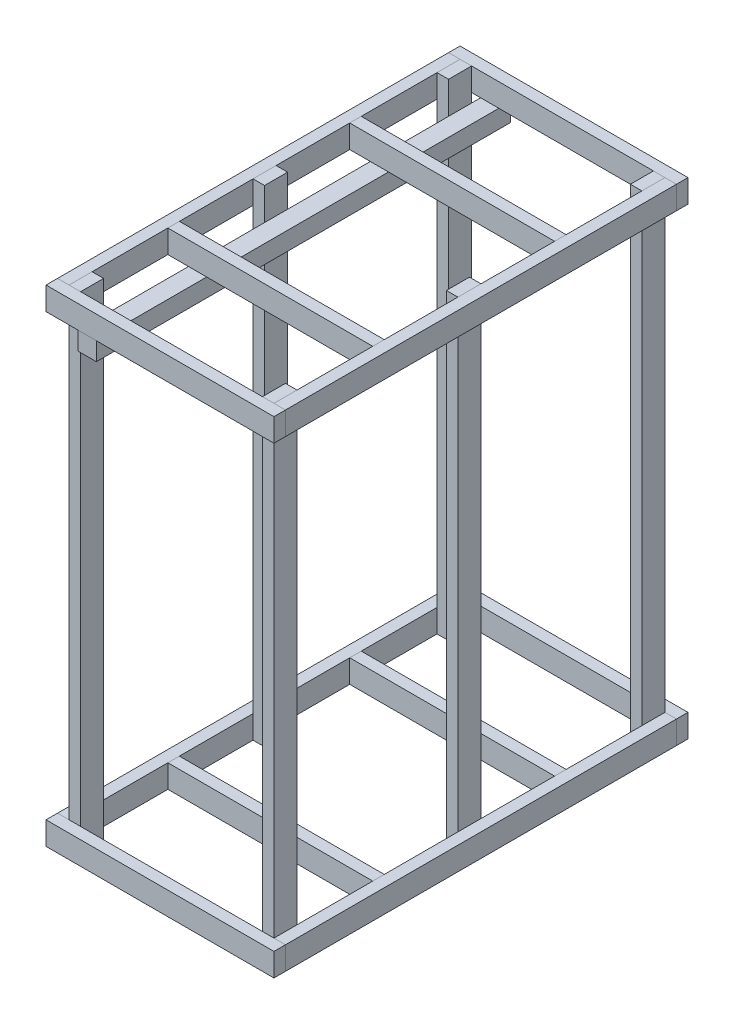
SolidWorks part; units mm, degrees
ref_plane "正面" through (0, 0, 0) normal (0, 0, 1) x (1, 0, 0)
ref_plane "平面" through (0, 0, 0) normal (0, 1, 0) x (1, 0, 0)
ref_plane "右側面" through (0, 0, 0) normal (1, 0, 0) x (0, 0, -1)
sketch "元ライン_正面" plane through (0, 0, 0) normal (0, 0, 1) x (1, 0, 0)
  line B0 (-135, 666) -> (-135, 0)
  line B1 (-135, 666) -> (105, 666)
  line B2 (105, 696) -> (135, 696)
  line B3 (105, 666) -> (105, 696)
  line B4 (-135, 0) -> (135, 0)
  line B5 (135, 696) -> (135, 0)
sketch_block_instance "ﾌﾞﾛｯｸ1-1"
sketch_block "ﾌﾞﾛｯｸ1"
sketch "元ライン_側面" plane through (0, 0, 0) normal (1, 0, 0) x (0, 0, -1)
  line B0 (-307.5, 696) -> (-307.5, 0)
  line B1 (-307.5, 696) -> (307.5, 696)
  line B2 (-307.5, 0) -> (307.5, 0)
  line B3 (307.5, 0) -> (307.5, 696)
sketch_block_instance "ﾌﾞﾛｯｸ2-1"
sketch_block "ﾌﾞﾛｯｸ2"
sketch "元ライン_平面" plane through (0, 0, 0) normal (0, 1, 0) x (1, 0, 0)
  line B0 (135, 307.5) -> (-135, 307.5)
  line B1 (-135, 307.5) -> (-135, -307.5)
  line B2 (-135, -307.5) -> (135, -307.5)
  line B3 (135, -307.5) -> (135, 307.5)
sketch_block_instance "ﾌﾞﾛｯｸ3-1"
sketch_block "ﾌﾞﾛｯｸ3"
sketch "マスター_平面" plane through (0, 0, 0) normal (0, 1, 0) x (1, 0, 0)
  line L10 (-188, 341.5) -> (-188, -341.5)
  line L11 (-188, -341.5) -> (188, -341.5)
  line L12 (188, -341.5) -> (188, 341.5)
  line L13 (188, 341.5) -> (-188, 341.5)
  line L14 (-135, -307.5) -> (135, -307.5) construction
  line L15 (135, 307.5) -> (-135, 307.5) construction
  line L16 (135, -307.5) -> (135, 307.5) construction
  line L17 (0, 307.5) -> (0, -307.5) construction
  line L18 (-188, -322.5) -> (188, -322.5)
  line L19 (169, -322.5) -> (169, 322.5)
  line L20 (188, 322.5) -> (-188, 322.5)
  line L21 (-169, 322.5) -> (-169, -322.5)
  line L22 (169, 322.5) -> (-169, 322.5) construction
  line L23 (-169, -322.5) -> (169, -322.5) construction
  line L25 (-169, 322.5) -> (-150, 322.5)
  line L26 (-169, 322.5) -> (-169, 284.5)
  line L27 (-169, 284.5) -> (-150, 284.5)
  line L28 (-150, 322.5) -> (-150, 284.5)
  dimension "D1" = 15
  dimension "D3" = 15
  dimension "D4" = 34
  dimension "D5" = 19
  dimension "D6" = 38
  dimension "D2" = 19
sketch "マスター_正面" plane through (0, 0, 0) normal (0, 0, 1) x (1, 0, 0)
  line L9 (-135, 0) -> (135, 0) construction
  line L10 (105, 696) -> (135, 696) construction
  line B0 (-188, -20) -> (-169, -20)
  line B1 (-188, -20) -> (-188, -58)
  line B2 (-188, -58) -> (-169, -58)
  line B3 (-169, -20) -> (-169, -58)
  line B4 (-188, 744) -> (-169, 744)
  line B5 (-188, 744) -> (-188, 706)
  line B6 (-188, 706) -> (-169, 706)
  line B7 (-169, 744) -> (-169, 706)
  line B8 (169, 744) -> (188, 744)
  line B9 (169, 744) -> (169, 706)
  line B10 (169, 706) -> (188, 706)
  line B11 (188, 744) -> (188, 706)
  line B12 (169, -20) -> (188, -20)
  line B13 (169, -20) -> (169, -58)
  line B14 (169, -58) -> (188, -58)
  line B15 (188, -20) -> (188, -58)
  dimension "D1" = 20
  dimension "D2" = 10
sketch_block_instance "ﾌﾞﾛｯｸ4-1"
sketch_block "ﾌﾞﾛｯｸ4" parameters "D1"=19, "D2"=38
sketch_block_instance "ﾌﾞﾛｯｸ4-2"
sketch_block_instance "ﾌﾞﾛｯｸ4-3"
sketch_block_instance "ﾌﾞﾛｯｸ4-4"
sketch "マスター_側面" plane through (0, 0, 0) normal (1, 0, 0) x (0, 0, -1)
  point P0 (350.1615, 370.0994)
  line B0 (-341.5, -20) -> (-322.5, -20)
  line B1 (-341.5, -20) -> (-341.5, -58)
  line B2 (-341.5, -58) -> (-322.5, -58)
  line B3 (-322.5, -20) -> (-322.5, -58)
  line B4 (322.5, -20) -> (341.5, -20)
  line B5 (322.5, -20) -> (322.5, -58)
  line B6 (322.5, -58) -> (341.5, -58)
  line B7 (341.5, -20) -> (341.5, -58)
  line B8 (322.5, 744) -> (341.5, 744)
  line B9 (322.5, 744) -> (322.5, 706)
  line B10 (322.5, 706) -> (341.5, 706)
  line B11 (341.5, 744) -> (341.5, 706)
  line B12 (-341.5, 744) -> (-322.5, 744)
  line B13 (-341.5, 744) -> (-341.5, 706)
  line B14 (-341.5, 706) -> (-322.5, 706)
  line B15 (-322.5, 744) -> (-322.5, 706)
sketch_block_instance "ﾌﾞﾛｯｸ5-1"
sketch_block "ﾌﾞﾛｯｸ5" parameters "D1"=19, "D2"=38
sketch_block_instance "ﾌﾞﾛｯｸ5-2"
sketch_block_instance "ﾌﾞﾛｯｸ5-3"
sketch_block_instance "ﾌﾞﾛｯｸ5-4"
sketch "ｽｹｯﾁ6" plane through (0, 0, 0) normal (0, 0, 1) x (1, 0, 0)
  line L4 (-169, -20) -> (-169, -58) construction
  line L5 (-188, -58) -> (-169, -58) construction
  line L6 (-188, -20) -> (-188, -58) construction
  line L7 (-188, -20) -> (-169, -20) construction
  line L8 (169, -58) -> (188, -58) construction
  line L9 (188, -20) -> (188, -58) construction
  line L10 (169, -20) -> (169, -58) construction
  line L11 (169, -20) -> (188, -20) construction
  line L12 (-169, -20) -> (-169, -58)
  line L13 (-188, -58) -> (-169, -58)
  line L14 (-188, -20) -> (-188, -58)
  line L15 (-188, -20) -> (-169, -20)
  line L16 (188, 744) -> (188, 706) construction
  line L17 (169, 706) -> (188, 706) construction
  line L18 (169, 744) -> (188, 744) construction
  line L19 (169, 744) -> (169, 706) construction
  line L20 (-188, 706) -> (-169, 706) construction
  line L21 (-169, 744) -> (-169, 706) construction
  line L22 (-188, 744) -> (-169, 744) construction
  line L23 (-188, 744) -> (-188, 706) construction
  line L24 (169, -58) -> (188, -58)
  line L25 (188, -20) -> (188, -58)
  line L26 (169, -20) -> (169, -58)
  line L27 (169, -20) -> (188, -20)
  line L28 (188, 744) -> (188, 706)
  line L29 (169, 706) -> (188, 706)
  line L30 (169, 744) -> (188, 744)
  line L31 (169, 744) -> (169, 706)
  line L32 (-188, 706) -> (-169, 706)
  line L33 (-169, 744) -> (-169, 706)
  line L34 (-188, 744) -> (-169, 744)
  line L35 (-188, 744) -> (-188, 706)
extrude "ﾎﾞｽ - 押し出し1" add sketch "ｽｹｯﾁ6" against normal up to vertex (322.5 mm away) and the other way up to vertex (322.5 mm away) up to point (188, 0, -322.5) other way up to point (188, 0, 322.5)
sketch "ｽｹｯﾁ8" plane through (0, 0, 0) normal (1, 0, 0) x (0, 0, -1)
  line L4 (-341.5, -20) -> (-341.5, -58) construction
  line L5 (-341.5, -58) -> (-322.5, -58) construction
  line L6 (-322.5, -20) -> (-322.5, -58) construction
  line L7 (-341.5, -20) -> (-322.5, -20) construction
  line L8 (-341.5, 706) -> (-322.5, 706) construction
  line L9 (-322.5, 744) -> (-322.5, 706) construction
  line L10 (-341.5, 744) -> (-322.5, 744) construction
  line L11 (-341.5, 744) -> (-341.5, 706) construction
  line L12 (-341.5, -20) -> (-341.5, -58)
  line L13 (-341.5, -58) -> (-322.5, -58)
  line L14 (-322.5, -20) -> (-322.5, -58)
  line L15 (-341.5, -20) -> (-322.5, -20)
  line L16 (322.5, 706) -> (341.5, 706) construction
  line L17 (341.5, 744) -> (341.5, 706) construction
  line L18 (322.5, 744) -> (341.5, 744) construction
  line L19 (322.5, 744) -> (322.5, 706) construction
  line L20 (322.5, -58) -> (341.5, -58) construction
  line L21 (341.5, -20) -> (341.5, -58) construction
  line L22 (322.5, -20) -> (341.5, -20) construction
  line L23 (322.5, -20) -> (322.5, -58) construction
  line L24 (-341.5, 706) -> (-322.5, 706)
  line L25 (-322.5, 744) -> (-322.5, 706)
  line L26 (-341.5, 744) -> (-322.5, 744)
  line L27 (-341.5, 744) -> (-341.5, 706)
  line L28 (322.5, 706) -> (341.5, 706)
  line L29 (341.5, 744) -> (341.5, 706)
  line L30 (322.5, 744) -> (341.5, 744)
  line L31 (322.5, 744) -> (322.5, 706)
  line L32 (322.5, -58) -> (341.5, -58)
  line L33 (341.5, -20) -> (341.5, -58)
  line L34 (322.5, -20) -> (341.5, -20)
  line L35 (322.5, -20) -> (322.5, -58)
extrude "ﾎﾞｽ - 押し出し2" add sketch "ｽｹｯﾁ8" along normal up to vertex (188 mm away) and the other way up to surface (188 mm away) separate body up to point (188, 0, 341.5) other way up to face at (-188, -39, 0)
sketch "ｽｹｯﾁ9" plane through (0, 0, 0) normal (0, 1, 0) x (1, 0, 0)
  line L0 (-169, 284.5) -> (-150, 284.5) construction
  line L1 (-169, 322.5) -> (-169, 284.5) construction
  line L2 (-150, 322.5) -> (-150, 284.5) construction
  line L3 (-169, 322.5) -> (-150, 322.5) construction
  line L4 (-169, 284.5) -> (-150, 284.5)
  line L5 (-169, 322.5) -> (-169, 284.5)
  line L6 (-150, 322.5) -> (-150, 284.5)
  line L7 (-169, 322.5) -> (-150, 322.5)
  line L8 (-169, -322.5) -> (-150, -322.5)
  line L9 (-169, -284.5) -> (-169, -322.5)
  line L10 (-169, -284.5) -> (-150, -284.5)
  line L11 (-150, -284.5) -> (-150, -322.5)
  line L12 (150, 284.5) -> (169, 284.5)
  line L13 (150, 322.5) -> (150, 284.5)
  line L14 (150, 322.5) -> (169, 322.5)
  line L15 (169, 322.5) -> (169, 284.5)
  line L16 (150, -322.5) -> (169, -322.5)
  line L17 (150, -284.5) -> (150, -322.5)
  line L18 (150, -284.5) -> (169, -284.5)
  line L19 (169, -284.5) -> (169, -322.5)
  line L20 (169, -322.5) -> (169, 322.5) construction
  line L21 (-188, -322.5) -> (188, -322.5) construction
  line L22 (-169, 19) -> (-169, -19)
  line L23 (-169, 19) -> (-150, 19)
  line L24 (-150, 19) -> (-150, -19)
  line L25 (-169, -19) -> (-150, -19)
  line L26 (150, 19) -> (150, -19)
  line L27 (150, 19) -> (169, 19)
  line L28 (169, 19) -> (169, -19)
  line L29 (150, -19) -> (169, -19)
  line L31 (-169, 322.5) -> (-169, -322.5) construction
  line L32 (-169, 0) -> (169, 0) construction
  line L33 (169, 322.5) -> (169, -322.5) construction
  point P28 (0, 0)
  point P31 (-169, 0)
extrude "縦材" add sketch "ｽｹｯﾁ9" along normal up to vertex and the other way up to vertex separate body
sketch "ｽｹｯﾁ10" plane through (0, 0, 0) normal (0, 0, 1) x (1, 0, 0)
  line L0 (-135, 666) -> (-135, 0) construction
  line L1 (-135, 706) -> (-105, 706)
  line L2 (-135, 706) -> (-135, 676)
  line L3 (-135, 676) -> (-105, 676)
  line L4 (-105, 706) -> (-105, 676)
  point P4 (-113.9049, 706)
  dimension "D1" = 30
extrude "ﾎﾞｽ - 押し出し4" add sketch "ｽｹｯﾁ10" along normal up to vertex and the other way up to vertex separate body
sketch "ｽｹｯﾁ11" plane through (0, 0, 0) normal (1, 0, 0) x (0, 0, -1)
  line L0 (-307.5, 696) -> (307.5, 696) construction
  line L1 (0, 696) -> (0, 0) construction
  line L5 (-307.5, 696) -> (307.5, 696) construction
  point P7 (0, 696)
  point P8 (-150, 706)
  line B0 (-159.5, 744) -> (-140.5, 744)
  line B1 (-159.5, 744) -> (-159.5, 706)
  line B2 (-159.5, 706) -> (-140.5, 706)
  line B3 (-140.5, 744) -> (-140.5, 706)
  line B4 (-159.5, -20) -> (-140.5, -20)
  line B5 (-159.5, -20) -> (-159.5, -58)
  line B6 (-159.5, -58) -> (-140.5, -58)
  line B7 (-140.5, -20) -> (-140.5, -58)
  line B8 (140.5, -20) -> (159.5, -20)
  line B9 (140.5, -20) -> (140.5, -58)
  line B10 (140.5, -58) -> (159.5, -58)
  line B11 (159.5, -20) -> (159.5, -58)
  line B12 (140.5, 744) -> (159.5, 744)
  line B13 (140.5, 744) -> (140.5, 706)
  line B14 (140.5, 706) -> (159.5, 706)
  line B15 (159.5, 744) -> (159.5, 706)
  dimension "D3" = 150
sketch_block_instance "ﾌﾞﾛｯｸ6-1"
sketch_block "ﾌﾞﾛｯｸ6" parameters "D1"=19, "D2"=38
sketch_block_instance "ﾌﾞﾛｯｸ6-2"
sketch_block_instance "ﾌﾞﾛｯｸ6-3"
sketch_block_instance "ﾌﾞﾛｯｸ6-4"
extrude "ﾎﾞｽ - 押し出し5" add sketch "ｽｹｯﾁ11" against normal up to vertex (169 mm away) and the other way up to vertex (169 mm away) separate body
